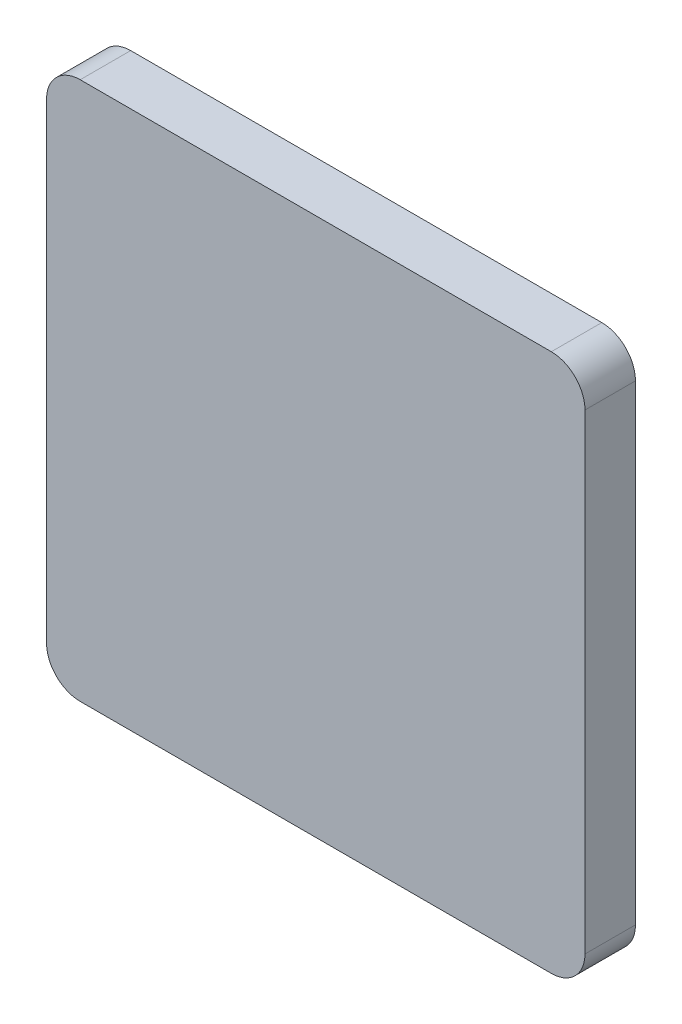
SolidWorks part; units mm, degrees
material "MDF"
ref_plane "Alzado" through (0, 0, 0) normal (0, 0, 1) x (1, 0, 0)
ref_plane "Planta" through (0, 0, 0) normal (0, 1, 0) x (1, 0, 0)
ref_plane "Vista lateral" through (0, 0, 0) normal (1, 0, 0) x (0, 0, -1)
sketch "Croquis1" plane through (0, 0, 0) normal (0, 0, 1) x (1, 0, 0)
  line L1 (-16, 16) -> (16, 16)
  line L2 (-16, 16) -> (-16, -16)
  line L3 (-16, -16) -> (16, -16)
  line L4 (16, 16) -> (16, -16)
  line L5 (-16, 16) -> (16, -16) construction
  line L6 (-16, -16) -> (16, 16) construction
  point P0 (0, 0)
  dimension "D1" = 32
  dimension "D2" = 32
extrude "Saliente-Extruir1" add sketch "Croquis1" along normal blind 3
fillet "Redondeo1" radius 2 4 edges at (16, -16, 1.5) (-16, -16, 1.5) (16, 16, 1.5) (-16, 16, 1.5)
